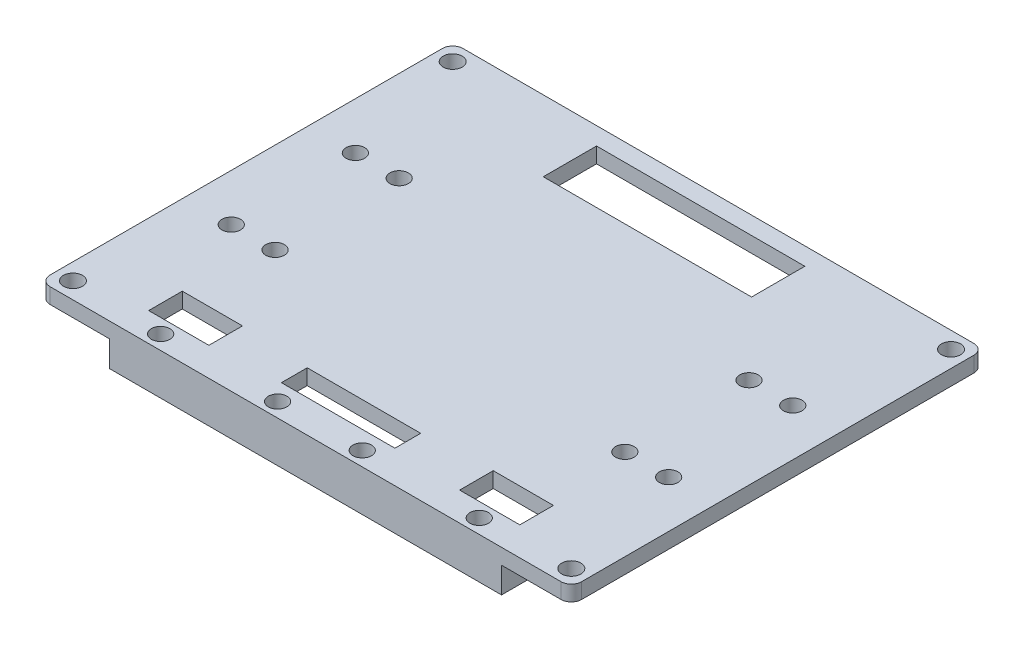
SolidWorks part; units mm, degrees
ref_plane "前视基准面" through (0, 0, 0) normal (0, 0, 1) x (1, 0, 0)
ref_plane "上视基准面" through (0, 0, 0) normal (0, 1, 0) x (1, 0, 0)
ref_plane "右视基准面" through (0, 0, 0) normal (1, 0, 0) x (0, 0, -1)
sketch "草图1" plane through (0, 0, 0) normal (0, 1, 0) x (1, 0, 0)
  line L0 (-51.5, 40) -> (-48.2968, 36.7968) construction
  line L1 (49.5, -40) -> (-49.5, -40)
  line L2 (51.5, -38) -> (51.5, 38)
  line L3 (49.5, 40) -> (-49.5, 40)
  line L4 (-51.5, -38) -> (-51.5, 38)
  line L5 (51.5, -40) -> (-51.5, 40) construction
  line L6 (51.5, 40) -> (-51.5, -40) construction
  line L7 (20.1874, 26.2491) -> (-20.1874, 26.2491)
  line L8 (20.1874, 26.2491) -> (20.1874, 36.5704)
  line L9 (20.1874, 36.5704) -> (-20.1874, 36.5704)
  line L10 (-20.1874, 26.2491) -> (-20.1874, 36.5704)
  line L11 (20.1874, 26.2491) -> (-20.1874, 36.5704) construction
  line L12 (20.1874, 36.5704) -> (-20.1874, 26.2491) construction
  line L13 (0, 31.4098) -> (0, -40) construction
  line L14 (51.5, 0) -> (-51.5, 0)
  line L16 (11, -33.6959) -> (-11, -33.6959)
  line L17 (11, -33.6959) -> (11, -28.6959)
  line L18 (11, -28.6959) -> (-11, -28.6959)
  line L19 (-11, -33.6959) -> (-11, -28.6959)
  line L20 (11, -33.6959) -> (-11, -28.6959) construction
  line L21 (11, -28.6959) -> (-11, -33.6959) construction
  line L26 (24.3014, -27.9372) -> (35.9691, -27.9372)
  line L27 (-24.3014, -34.4545) -> (-35.9691, -34.4545)
  line L31 (-24.3014, -34.4545) -> (-24.3014, -27.9372)
  line L32 (-24.3014, -27.9372) -> (-35.9691, -27.9372)
  line L33 (-35.9691, -34.4545) -> (-35.9691, -27.9372)
  line L34 (-24.3014, -34.4545) -> (-35.9691, -27.9372) construction
  line L35 (-24.3014, -27.9372) -> (-35.9691, -34.4545) construction
  line L36 (35.9691, -34.4545) -> (35.9691, -27.9372)
  line L37 (24.3014, -34.4545) -> (35.9691, -34.4545)
  line L38 (24.3014, -34.4545) -> (24.3014, -27.9372)
  line L39 (-48.2968, 36.7968) -> (-48.2968, -36.7968) construction
  line L47 (-38.1468, 18.3) -> (-38.1468, -18.3) construction
  line L48 (-38.1468, 18.3) -> (-38.1468, 12.03)
  line L49 (-33.9018, 12.03) -> (-42.3918, 12.03)
  circle A0 centre (-48.2968, 36.7968) radius 1.85
  circle A1 centre (48.2968, 36.7968) radius 1.85
  circle A2 centre (48.2968, -36.7968) radius 1.85
  circle A3 centre (-48.2968, -36.7968) radius 1.85
  arc A4 (-49.5, -40) -> (-51.5, -38) centre (-49.5, -38) cw
  arc A5 (49.5, -40) -> (51.5, -38) centre (49.5, -38) ccw
  arc A6 (51.5, 38) -> (49.5, 40) centre (49.5, 38) ccw
  arc A7 (-49.5, 40) -> (-51.5, 38) centre (-49.5, 38) ccw
  circle A8 centre (-42.3918, 12.03) radius 1.8
  circle A9 centre (-33.9018, 12.03) radius 1.8
  circle A10 centre (-33.9018, -12.03) radius 1.8
  circle A11 centre (-42.3918, -12.03) radius 1.8
  circle A12 centre (33.9018, -12.03) radius 1.8
  circle A13 centre (42.3918, -12.03) radius 1.8
  circle A14 centre (33.9018, 12.03) radius 1.8
  circle A15 centre (42.3918, 12.03) radius 1.8
  point P0 (0, 0)
  point P6 (0, 31.4098)
  point P18 (0, 0)
  point P36 (0, -31.1959)
  point P41 (-69.6672, -54.1104)
  point P42 (-30.1353, -31.1959)
  point P54 (-48.2968, 0)
  point P62 (-38.1468, 12.03)
  dimension "D4" = 2
  dimension "D1" = 103
  dimension "D2" = 80
  dimension "D3" = 45
extrude "凸台-拉伸1" add sketch "草图1" along normal blind 3 contours L3 A7 L4 L14 L2 A6 L7 L10 L9 L8 A0 A1 | L1 A5 L2 L14 L4 A4 A3 A2
ref_plane "基准面1" through (0, 3, 0) normal (0, 1, 0) x (1, 0, 0)
sketch "草图2" plane through (0, 3, 0) normal (0, 1, 0) x (1, 0, 0)
  line L0 (49.5, -40) -> (-49.5, -40) construction
  line L1 (-37.9691, -34.4545) -> (37.9691, -34.4545)
  line L2 (-37.9691, -34.4545) -> (-37.9691, -40)
  line L3 (-37.9691, -40) -> (37.9691, -40)
  line L4 (37.9691, -34.4545) -> (37.9691, -40)
  line L5 (0, -34.4545) -> (0, -40) construction
  point P13 (0, -37.2273)
  point P16 (0, -37.2273)
  dimension "D1" = 2
  dimension "D2" = 2
extrude "凸台-拉伸2" add sketch "草图2" against normal blind 8
ref_plane "基准面2" through (0, -5, 0) normal (0, -1, 0) x (-1, 0, 0)
sketch "草图3" plane through (0, -5, 0) normal (0, -1, 0) x (-1, 0, 0)
  line L0 (0, -40) -> (0, -34.4545) construction
  line L1 (37.9691, -40) -> (-37.9691, -40) construction
  line L2 (-37.9691, -34.4545) -> (37.9691, -34.4545) construction
  line L3 (15, -37.2273) -> (-15, -37.2273)
  line L4 (10, -37.2273) -> (-10, -37.2273)
  circle A0 centre (-8.2, -37.2273) radius 1.8
  circle A1 centre (8.2, -37.2273) radius 1.8
  circle A2 centre (-30.8751, -37.2273) radius 1.8
  circle A3 centre (30.8751, -37.2273) radius 1.8
  point P9 (0, -37.2273)
  point P12 (0, -37.2273)
  dimension "D1" = 20
extrude "切除-拉伸1" cut sketch "草图3" against normal blind 15 contours A3 | L3 A1 | L3 A1 | L4 A0 | A2
sketch "草图4" plane through (0, 3, 0) normal (0, 1, 0) x (1, 0, 0)
  line L1 (-44.1918, 12.03) -> (-51.3273, 12.03) construction
  circle A0 centre (-42.3918, 12.03) radius 1.8 construction
